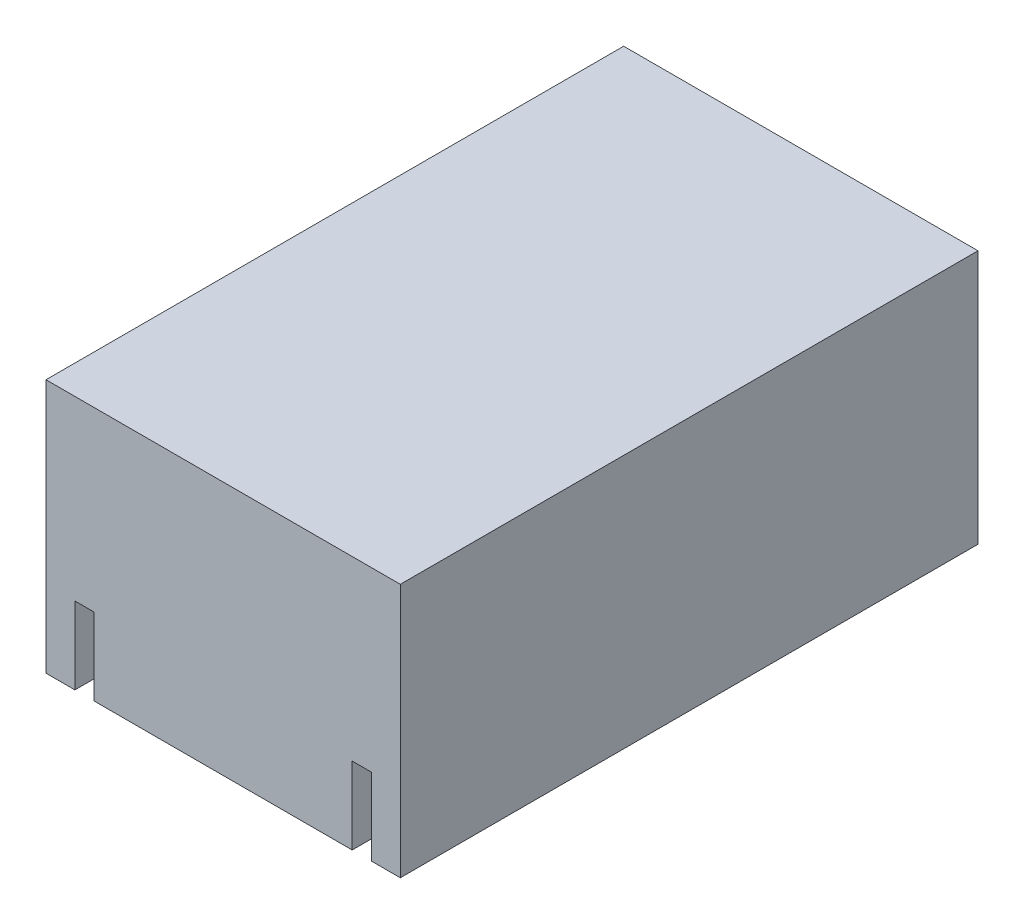
SolidWorks part; units mm, degrees
ref_plane "Ebene vorne" through (0, 0, 0) normal (0, 0, 1) x (1, 0, 0)
ref_plane "Ebene oben" through (0, 0, 0) normal (0, 1, 0) x (1, 0, 0)
ref_plane "Ebene rechts" through (0, 0, 0) normal (1, 0, 0) x (0, 0, -1)
sketch "Skizze1" plane through (0, 0, 0) normal (0, 0, 1) x (1, 0, 0)
  line L1 (23, -16.5) -> (-23, -16.5)
  line L2 (23, -16.5) -> (23, 16.5)
  line L3 (23, 16.5) -> (-23, 16.5)
  line L4 (-23, -16.5) -> (-23, 16.5)
  line L5 (23, -16.5) -> (-23, 16.5) construction
  line L6 (23, 16.5) -> (-23, -16.5) construction
  point P0 (0, 0)
  dimension "D1" = 33
  dimension "D2" = 46
extrude "Aufsatz-Linear austragen1" add sketch "Skizze1" along normal blind 75
sketch "Skizze2" plane through (0, 0, 75) normal (0, 0, 1) x (1, 0, 0)
  line L0 (-23, -16.5) -> (23, -16.5) construction
  line L1 (-16.75, -16.5) -> (-19.25, -16.5)
  line L2 (-16.75, -16.5) -> (-16.75, -6.5)
  line L3 (-16.75, -6.5) -> (-19.25, -6.5)
  line L4 (-19.25, -16.5) -> (-19.25, -6.5)
  line L5 (-16.75, -16.5) -> (-19.25, -6.5) construction
  line L6 (-16.75, -6.5) -> (-19.25, -16.5) construction
  line L7 (-18, -6.5) -> (18, -6.5) construction
  line L8 (16.75, -16.5) -> (19.25, -16.5)
  line L9 (16.75, -16.5) -> (16.75, -6.5)
  line L10 (16.75, -6.5) -> (19.25, -6.5)
  line L11 (19.25, -16.5) -> (19.25, -6.5)
  line L12 (16.75, -16.5) -> (19.25, -6.5) construction
  line L13 (16.75, -6.5) -> (19.25, -16.5) construction
  line L14 (0, 0) -> (0, -16.5) construction
  point P4 (-18, -11.5)
  point P11 (18, -11.5)
  point P17 (0, -6.5)
  dimension "D1" = 36
  dimension "D2" = 2.5
  dimension "D3" = 10
extrude "Schnitt-Linear austragen1" cut sketch "Skizze2" against normal through all
